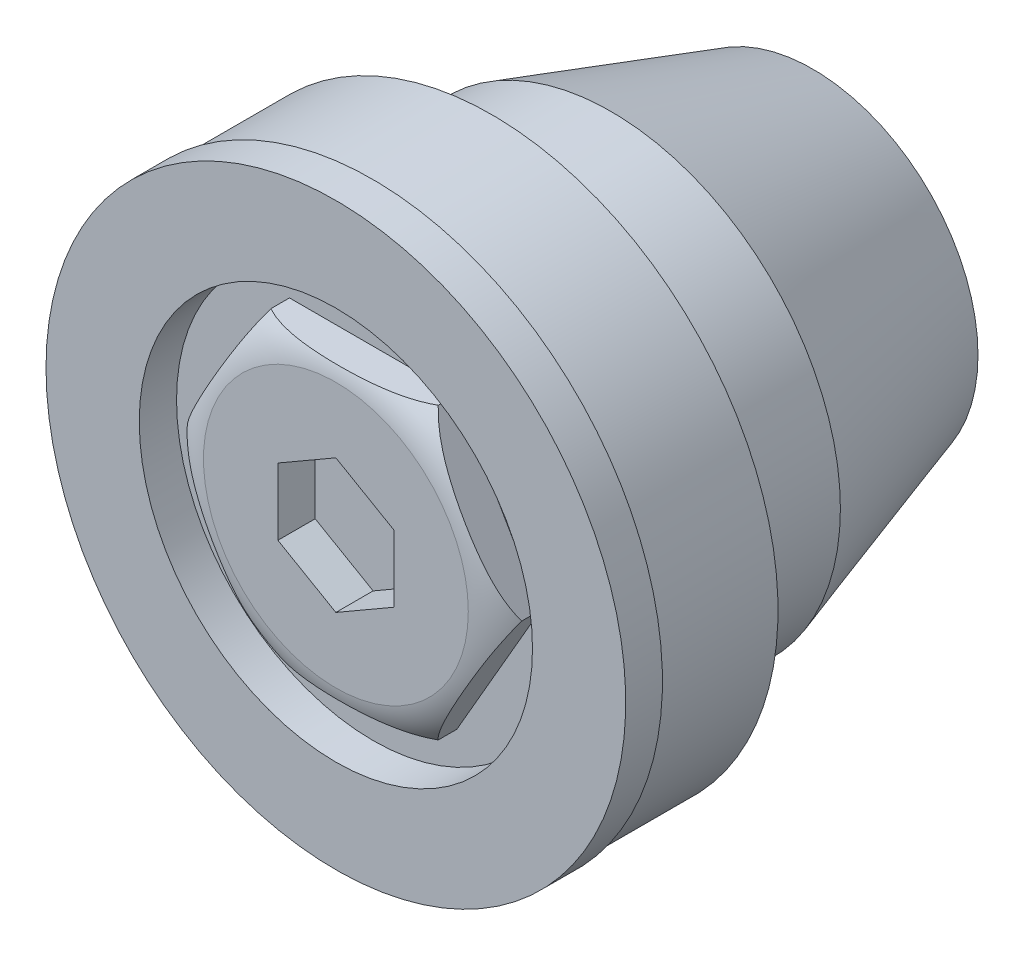
SolidWorks part; units mm, degrees
ref_plane "Front Plane" through (0, 0, 0) normal (0, 0, 1) x (1, 0, 0)
ref_plane "Top Plane" through (0, 0, 0) normal (0, 1, 0) x (1, 0, 0)
ref_plane "Right Plane" through (0, 0, 0) normal (1, 0, 0) x (0, 0, -1)
sketch "Sketch1" plane through (0, 0, 0) normal (1, 0, 0) x (0, 0, -1)
  line L0 (0, 0) -> (0, 15.8)
  line L1 (0, 15.8) -> (2, 15.8)
  line L2 (2, 15.8) -> (2, 15.6)
  line L3 (2, 15.6) -> (8.5, 15.6)
  line L4 (8.5, 15.6) -> (8.5, 12.5)
  line L5 (8.5, 12.5) -> (15, 12.5)
  line L6 (15, 12.5) -> (26, 9)
  line L7 (26, 9) -> (26, 0)
  line L8 (26, 0) -> (0, 0)
  line L9 (0, 0) -> (-50000, 0) construction
  dimension "D1" = 31.6
  dimension "D2" = 2
  dimension "D3" = 6.5
  dimension "D4" = 0.2
  dimension "D5" = 6.5
  dimension "D6" = 25
  dimension "D7" = 26
  dimension "D8" = 18
revolve "Revolve1" add sketch "Sketch1" angle 360 about L9
sketch "Sketch2" plane through (0, 0, -26) normal (0, 0, -1) x (-1, 0, 0)
  circle A0 centre (0, 0) radius 5.7
  dimension "D1" = 11.4
extrude "Cut-Extrude1" cut sketch "Sketch2" against normal blind 17.78
sketch "Sketch3" plane through (0, 0, 0) normal (0, 0, 1) x (1, 0, 0)
  line L1 (4.5611, 7.9) -> (-4.5611, 7.9)
  line L2 (-4.5611, 7.9) -> (-9.1221, 0)
  line L3 (-9.1221, 0) -> (-4.5611, -7.9)
  line L4 (-4.5611, -7.9) -> (4.5611, -7.9)
  line L5 (4.5611, -7.9) -> (9.1221, 0)
  line L6 (9.1221, 0) -> (4.5611, 7.9)
  circle A0 centre (0, 0) radius 7.9 construction
  circle A1 centre (0, 0) radius 10.7172
  dimension "D2" = 21.4344
  dimension "D1" = 15.8
extrude "Cut-Extrude2" cut sketch "Sketch3" against normal blind 2.032
sketch "Sketch4" plane through (0, 0, 0) normal (0, 1, 0) x (1, 0, 0)
  line L0 (-9.1221, 2.032) -> (-9.1221, 0) construction
  line L1 (-4.5611, 0) -> (-9.1221, 0) construction
  line L2 (-9.1221, 1.016) -> (-9.1221, 0)
  line L3 (-9.1221, 0) -> (-6.5157, 0)
  line L4 (0, 0) -> (0, 2.6484) construction
  line L5 (-9.1221, 0) -> (-7.2177, 0)
  arc A0 (-9.1221, 1.016) -> (-7.2177, 0) centre (-6.7535, 3.163) ccw
  dimension "D1" = 1.9044
revolve "Cut-Revolve1" cut sketch "Sketch4" angle 360 about L4
sketch "Sketch5" plane through (0, 0, 0) normal (0, 0, 1) x (1, 0, 0)
  line L1 (0, 3.6489) -> (-3.16, 1.8244)
  line L2 (-3.16, 1.8244) -> (-3.16, -1.8244)
  line L3 (-3.16, -1.8244) -> (0, -3.6489)
  line L4 (0, -3.6489) -> (3.16, -1.8244)
  line L5 (3.16, -1.8244) -> (3.16, 1.8244)
  line L6 (3.16, 1.8244) -> (0, 3.6489)
  circle A0 centre (0, 0) radius 3.16 construction
  dimension "D1" = 6.32
extrude "Cut-Extrude3" cut sketch "Sketch5" against normal blind 2.032
